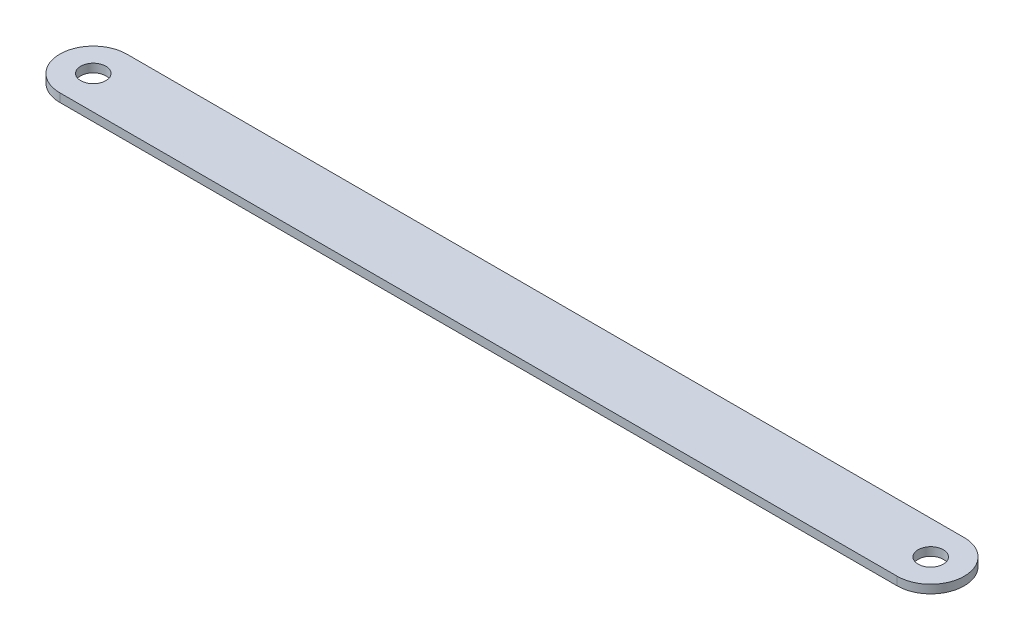
SolidWorks part; units mm, degrees
material "201 Annealed Stainless Steel (SS)"
ref_plane "Front Plane" through (0, 0, 0) normal (0, 0, 1) x (1, 0, 0)
ref_plane "Top Plane" through (0, 0, 0) normal (0, 1, 0) x (1, 0, 0)
ref_plane "Right Plane" through (0, 0, 0) normal (1, 0, 0) x (0, 0, -1)
sketch "Sketch1" plane through (0, 0, 0) normal (0, 1, 0) x (1, 0, 0)
  line L0 (50, 0) -> (-50, 0) construction
  line L1 (50, -4) -> (-50, -4)
  line L2 (50, 4) -> (-50, 4)
  arc A0 (50, -4) -> (50, 4) centre (50, 0) ccw
  arc A1 (-50, 4) -> (-50, -4) centre (-50, 0) ccw
  circle A2 centre (-50, 0) radius 1.5
  circle A3 centre (50, 0) radius 1.5
  point P2 (0, 0)
  dimension "D3" = 3
  dimension "D4" = 3
  dimension "D1" = 8
  dimension "D2" = 100
extrude "Boss-Extrude1" add sketch "Sketch1" along normal blind 1
